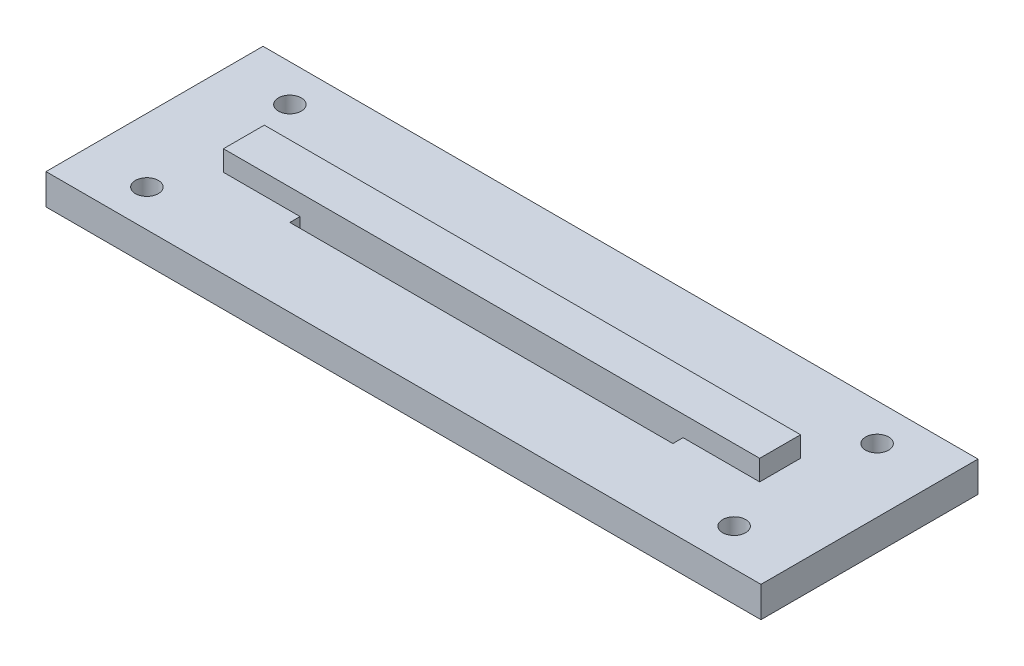
SolidWorks part; units mm, degrees
ref_plane "前视基准面" through (0, 0, 0) normal (0, 0, 1) x (1, 0, 0)
ref_plane "上视基准面" through (0, 0, 0) normal (0, 1, 0) x (1, 0, 0)
ref_plane "右视基准面" through (0, 0, 0) normal (1, 0, 0) x (0, 0, -1)
other "Configuration Table"
sketch "01_Base_Profile" plane through (0, 0, 0) normal (0, 1, 0) x (1, 0, 0)
  line L1 (-140, -42.5) -> (140, -42.5)
  line L2 (-140, -42.5) -> (-140, 42.5)
  line L3 (-140, 42.5) -> (140, 42.5)
  line L4 (140, -42.5) -> (140, 42.5)
  line L5 (-140, -42.5) -> (140, 42.5) construction
  line L6 (-140, 42.5) -> (140, -42.5) construction
  line L7 (-75, -12) -> (75, -12)
  line L8 (-75, -12) -> (-75, 12)
  line L9 (-75, 12) -> (75, 12)
  line L10 (75, -12) -> (75, 12)
  line L11 (-75, -12) -> (75, 12) construction
  line L12 (-75, 12) -> (75, -12) construction
  circle A0 centre (-115, -28) radius 4.5
  circle A1 centre (115, -28) radius 4.5
  circle A2 centre (-115, 28) radius 4.5
  circle A3 centre (115, 28) radius 4.5
  point P0 (0, 0)
  point P14 (0, 0)
extrude "01_Base_Extrude" add sketch "01_Base_Profile" along normal blind 12
sketch "02_Boss_Profile" plane through (0, 0, 0) normal (0, 1, 0) x (1, 0, 0)
  line L1 (-105, -8) -> (105, -8)
  line L2 (-105, -8) -> (-105, 8)
  line L3 (-105, 8) -> (105, 8)
  line L4 (105, -8) -> (105, 8)
  line L5 (-105, -8) -> (105, 8) construction
  line L6 (-105, 8) -> (105, -8) construction
  point P0 (0, 0)
extrude "02_Reinforcement_Boss" add sketch "02_Boss_Profile" along normal blind 20
